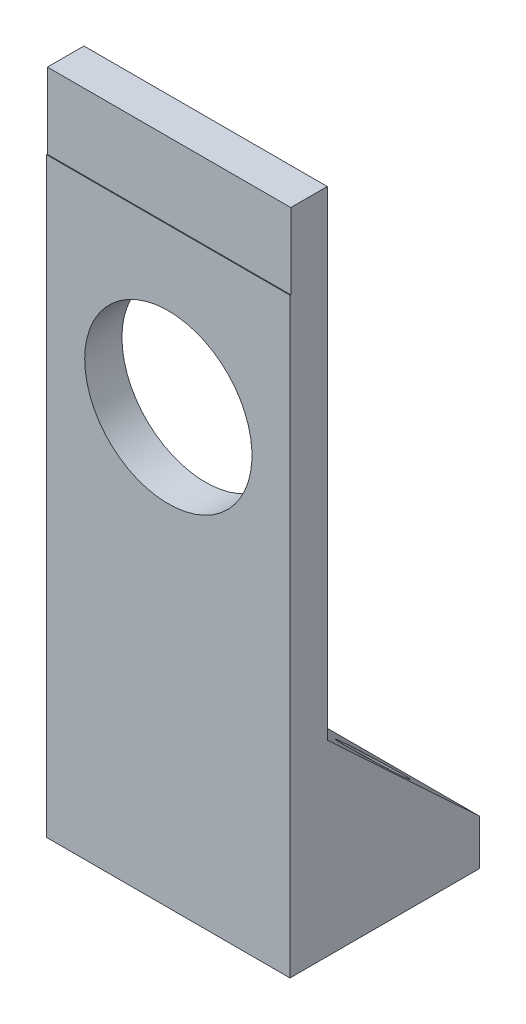
SolidWorks part; units mm, degrees
material "ABS"
ref_plane "Front Plane" through (0, 0, 0) normal (0, 0, 1) x (1, 0, 0)
ref_plane "Top Plane" through (0, 0, 0) normal (0, 1, 0) x (1, 0, 0)
ref_plane "Right Plane" through (0, 0, 0) normal (1, 0, 0) x (0, 0, -1)
sketch "Sketch1" plane through (0, 0, 0) normal (0, 0, 1) x (1, 0, 0)
  line L0 (-24, 15) -> (0, 15)
  line L1 (0, 15) -> (0, 0)
  line L2 (0, 0) -> (93, 0)
  line L3 (93, 0) -> (93, 102.7)
  line L4 (93, 102.7) -> (0, 102.7)
  line L5 (0, 102.7) -> (0, 30)
  line L6 (0, 30) -> (-24, 30)
  line L7 (-24, 30) -> (-24, 15)
  circle A0 centre (15, 10.5) radius 8
  circle A1 centre (70, 72) radius 11
  circle A2 centre (15, 10.5) radius 11
  dimension "D1" = 15
  dimension "D10" = 16
  dimension "D11" = 22
  dimension "D12" = 22
  dimension "D2" = 24
  dimension "D3" = 72.7
  dimension "D4" = 15
  dimension "D5" = 15
  dimension "D6" = 10.5
  dimension "D7" = 82.5061
  dimension "D8" = 72
  dimension "D9" = 93
extrude "Boss-Extrude1" add sketch "Sketch1" along normal blind 4.8 contours A2 L2 L3 L4 L5 L6 L7 L0 L1 A1 | L2 A2 A0
sketch "Sketch2" plane through (0, 0, 4.8) normal (0, 0, 1) x (1, 0, 0)
  line L0 (93, 0) -> (93, 102.7) construction
  line L1 (48.1786, 92.7632) -> (93, 92.7632)
  line L2 (48.1786, 92.7632) -> (48.1786, 52.666)
  line L3 (48.1786, 52.666) -> (93, 52.666)
  line L4 (93, 92.7632) -> (93, 52.666)
  line L5 (48.1786, 92.7632) -> (93, 52.666) construction
  line L6 (48.1786, 52.666) -> (93, 92.7632) construction
  circle A0 centre (70, 72) radius 11
  circle A1 centre (70, 72) radius 4.15
  point P8 (70.5893, 72.7146)
  line M4 (93, 0) -> (93, 102.7)
  circle M10 centre (70, 72) radius 11
  dimension "D1" = 22
  dimension "D2" = 8.3
extrude "Boss-Extrude2" add sketch "Sketch2" along normal blind 8.2 contours L2 L3 L1 M4 M10
sketch "Sketch3" plane through (0, 0, 4.8) normal (0, 0, 1) x (1, 0, 0)
  line L1 (-24, 15) -> (0, 15)
  line L2 (-24, 15) -> (-24, 30)
  line L3 (-24, 30) -> (0, 30)
  line L4 (0, 15) -> (0, 30)
  line L5 (-24, 15) -> (0, 30) construction
  line L6 (-24, 30) -> (0, 15) construction
  line L7 (0, 0) -> (93, 0)
  line L8 (0, 0) -> (0, 52.666)
  line L9 (0, 52.666) -> (93, 52.666)
  line L10 (93, 0) -> (93, 52.666)
  line L11 (0, 0) -> (93, 52.666) construction
  line L12 (0, 52.666) -> (93, 0) construction
  circle A0 centre (15, 10.5) radius 8
  point P4 (-12, 22.5)
  point P11 (46.5, 26.333)
  circle M1 centre (15, 10.5) radius 8
  line M6 (0, 102.7) -> (0, 30)
  line M7 (0, 30) -> (-24, 30)
  line M8 (-24, 30) -> (-24, 15)
  line M9 (-24, 15) -> (0, 15)
  line M10 (0, 15) -> (0, 0)
  line M11 (0, 0) -> (93, 0)
  line M12 (93, 0) -> (93, 52.666)
  line M13 (93, 52.666) -> (48.1786, 52.666)
extrude "Boss-Extrude3" add sketch "Sketch3" along normal blind 5 contours L4 M9 M7 M8 | L9 L4 M6 M10 M11 M12 M13 M1
sketch "Sketch4" plane through (0, 75.2347, 0) normal (0, -1, 0) x (1, 0, 0)
  line L0 (0, 9.8) -> (0, 4.8) construction
  line L1 (0, 4.8) -> (48.1786, 4.8)
  line L2 (0, 4.8) -> (0, 45.3)
  line L3 (0, 45.3) -> (48.1786, 45.3)
  line L4 (48.1786, 4.8) -> (48.1786, 45.3)
  line L5 (0, 4.8) -> (48.1786, 45.3) construction
  line L6 (0, 45.3) -> (48.1786, 4.8) construction
  line L7 (0, 4.8) -> (48.1786, 4.8) construction
  line L8 (48.1786, 13) -> (48.1786, 9.8) construction
  line L9 (0, 0) -> (93, 0) construction
  line L10 (0, 45.3) -> (-5, 45.3)
  line L11 (0, 45.3) -> (0, 0)
  line L12 (0, 0) -> (-5, 0)
  line L13 (-5, 45.3) -> (-5, 0)
  line L14 (0, 45.3) -> (-5, 0) construction
  line L15 (0, 0) -> (-5, 45.3) construction
  circle A0 centre (38.3604, 30.3) radius 6.35
  circle A1 centre (38.3604, 23.3) radius 18.5
  circle A3 centre (53.8604, 23.3) radius 2
  circle A4 centre (46.1104, 9.8766) radius 2
  circle A5 centre (30.6104, 9.8766) radius 2
  point P10 (24.0893, 25.05)
  point P30 (-2.5, 22.65)
  dimension "D1" = 12.7
  dimension "D2" = 15
  dimension "D3" = 4
  dimension "D4" = 4
  dimension "D5" = 4
  dimension "D6" = 5
  dimension "D7" = 0
extrude "Boss-Extrude4" add sketch "Sketch4" along normal blind 5
sketch "Sketch5" plane through (48.1786, 0, 0) normal (1, 0, 0) x (0, 0, -1)
  line L0 (-45.3, 75.2347) -> (-13, 92.7632)
  line L1 (-13, 92.7632) -> (-4.8, 92.7632)
  line L2 (-4.8, 92.7632) -> (-4.8, 70.2347)
  line L3 (-4.8, 70.2347) -> (-45.3, 70.2347)
  line L4 (-45.3, 70.2347) -> (-45.3, 75.2347)
extrude "Boss-Extrude5" add sketch "Sketch5" against normal blind 5
sketch "Sketch6" plane through (0, 0, 4.8) normal (0, 0, 1) x (1, 0, 0)
  line L0 (0, 70.2347) -> (0, 52.666) construction
  line L1 (0, 70.2347) -> (48.1786, 70.2347)
  line L2 (0, 70.2347) -> (0, 52.666)
  line L3 (0, 52.666) -> (48.1786, 52.666)
  line L4 (48.1786, 70.2347) -> (48.1786, 52.666)
  line L5 (0, 70.2347) -> (48.1786, 52.666) construction
  line L6 (0, 52.666) -> (48.1786, 70.2347) construction
  line L7 (0, 70.2347) -> (48.1786, 70.2347) construction
  point P4 (24.0893, 61.4504)
extrude "Boss-Extrude6" add sketch "Sketch6" along normal up to surface (5 mm away)
sketch "Sketch8" plane through (0, 30, 0) normal (0, 1, 0) x (1, 0, 0)
  line L0 (0, 0) -> (-24, -9.8)
  line L1 (-24, -9.8) -> (-24, 0)
  line L2 (-24, 0) -> (0, -9.8)
  circle A0 centre (-12, -4.9) radius 2
  dimension "D1" = 4
extrude "Cut-Extrude1" cut sketch "Sketch8" against normal through all contours A0
sketch "Sketch9" plane through (0, 0, 9.8) normal (0, 0, 1) x (1, 0, 0)
  line L1 (0, 15) -> (93, 15)
  line L2 (0, 15) -> (0, 0)
  line L3 (0, 0) -> (93, 0)
  line L4 (93, 15) -> (93, 0)
extrude "Cut-Extrude2" cut sketch "Sketch9" against normal blind 100
sketch "Sketch11" plane through (0, 0, 0) normal (0, 0, -1) x (-1, 0, 0)
  line L0 (-93, 102.7) -> (0, 102.7) construction
  line L1 (-54, 102.7) -> (24, 102.7)
  line L2 (-54, 102.7) -> (-54, 15)
  line L3 (-54, 15) -> (24, 15)
  line L4 (24, 102.7) -> (24, 15)
  line L9 (-59.2, 73.9635) -> (-59.2, 74.0879)
  circle A0 centre (-70, 72) radius 11 construction
  line M7 (-93, 15) -> (-21.6144, 15)
  arc M8 (-21.6144, 15) -> (-8.3856, 15) centre (-15, 10.5) cw
  line M9 (-8.3856, 15) -> (24, 15)
  line M10 (24, 15) -> (24, 30)
  line M11 (24, 30) -> (0, 30)
  line M12 (0, 30) -> (0, 102.7)
  line M13 (0, 102.7) -> (-93, 102.7)
  dimension "D1" = 16
extrude "Cut-Extrude3" cut sketch "Sketch11" against normal blind 100 contours L2 M13 M7 M8 M9 M10 M11 M12
sketch "Sketch12" plane through (0, 0, 0) normal (0, 0, -1) x (-1, 0, 0)
  line L0 (-93, 15) -> (-54, 15) construction
  line L1 (-93, 102.7) -> (-86, 102.7)
  line L2 (-93, 102.7) -> (-93, 15)
  line L3 (-93, 15) -> (-86, 15)
  line L4 (-86, 102.7) -> (-86, 15)
  circle A0 centre (-70, 72) radius 11 construction
  dimension "D1" = 16
extrude "Cut-Extrude4" cut sketch "Sketch12" against normal blind 100
sketch "Sketch13" plane through (86, 0, 0) normal (1, 0, 0) x (0, 0, -1)
  line L0 (0, 15) -> (-9.8, 15) construction
  line L1 (-13, 92.7632) -> (-4.9, 92.7632)
  line L2 (-13, 92.7632) -> (-13, 15)
  line L3 (-13, 15) -> (-4.9, 15)
  line L4 (-4.9, 92.7632) -> (-4.9, 15)
extrude "Cut-Extrude5" cut sketch "Sketch13" against normal blind 100
sketch "Sketch14" plane through (0, 0, 0) normal (0, 0, -1) x (-1, 0, 0)
  line L0 (-54, 102.7) -> (-54, 15) construction
  line L1 (-86, 15) -> (-54, 15)
  line L2 (-86, 15) -> (-86, 21)
  line L3 (-86, 21) -> (-54, 21)
  line L4 (-54, 15) -> (-54, 21)
  dimension "D1" = 6
extrude "Boss-Extrude7" add sketch "Sketch14" along normal blind 20
sketch "Sketch15" plane through (0, 21, 0) normal (0, 1, 0) x (1, 0, 0)
  line L0 (86, 20) -> (86, 0) construction
  line L1 (54, 20) -> (86, 20) construction
  circle A0 centre (80, 12) radius 2
  circle A1 centre (60, 12) radius 2
  dimension "D1" = 20
  dimension "D2" = 6
  dimension "D3" = 4
  dimension "D4" = 4
  dimension "D5" = 0
  dimension "D6" = 8
extrude "Cut-Extrude6" cut sketch "Sketch15" against normal blind 14
sketch "Sketch19" plane through (86, 0, 0) normal (1, 0, 0) x (0, 0, -1)
  line L0 (20, 21) -> (0, 39.6315)
  line L1 (0, 21) -> (0, 102.7) construction
  line L2 (0, 39.6315) -> (0, 21)
  line L3 (0, 21) -> (20, 21)
extrude "Boss-Extrude10" add sketch "Sketch19" against normal blind 32
sketch "Sketch22" plane through (0, 21, 0) normal (0, -1, 0) x (1, 0, 0)
  circle A0 centre (80, -12) radius 3.5
  circle A1 centre (60, -12) radius 3.5
  dimension "D1" = 7
  dimension "D2" = 7
extrude "Cut-Extrude7" cut sketch "Sketch22" against normal blind 32
